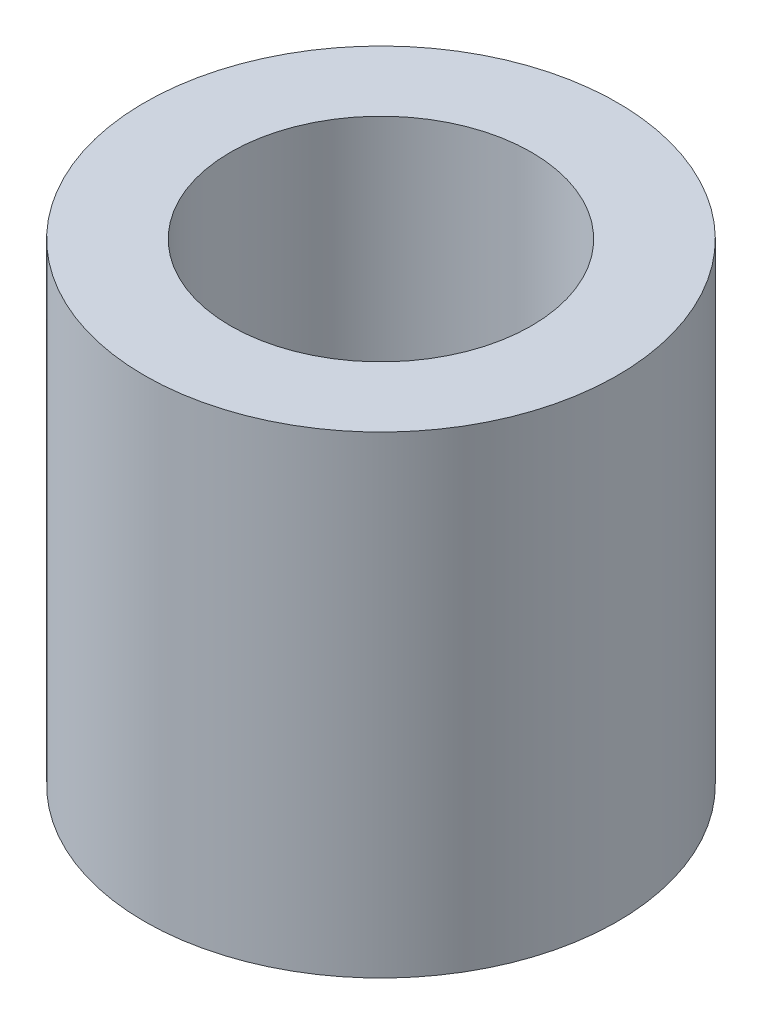
SolidWorks part; units mm, degrees
ref_plane "Front Plane" through (0, 0, 0) normal (0, 0, 1) x (1, 0, 0)
ref_plane "Top Plane" through (0, 0, 0) normal (0, 1, 0) x (1, 0, 0)
ref_plane "Right Plane" through (0, 0, 0) normal (1, 0, 0) x (0, 0, -1)
sketch "Sketch1" plane through (0, 0, 0) normal (0, 1, 0) x (1, 0, 0)
  circle A0 centre (0, 0) radius 2.75
  dimension "D1" = 5.5
extrude "Boss-Extrude1" add sketch "Sketch1" along normal blind 5.5 contours A0
hole_wizard "Ø3.5 (3.5) Diameter Hole1" positions "3DSketch1" profile "Sketch2" hole size "Ø3.5" standard "ANSI Metric" end condition through all
sketch3d "3DSketch1"
  line L0 (0, 5.5, 0) -> (0, 0, 0) construction
  point P0 (0, 0, 0)
  point P3 (0, 0, 0)
  point P5 (0, 0, 0)
  point P8 (0, 0, 0)
  point P10 (0, 5.5, 0)
sketch "Sketch2" plane through (0, 5.5, 0) normal (1, 0, 0) x (0, 0, 1)
  line L0 (0, 0) -> (0, 5.5)
  line L1 (0, 5.5) -> (1.75, 5.5)
  line L2 (1.75, 5.5) -> (1.75, 0)
  line L5 (1.75, 0) -> (0, 0)
  line L11 (0, -6.35) -> (0, 107.95) construction
  dimension "Thru Hole Dia." = 3.5
  dimension "Thru Hole Depth" = 5.5
